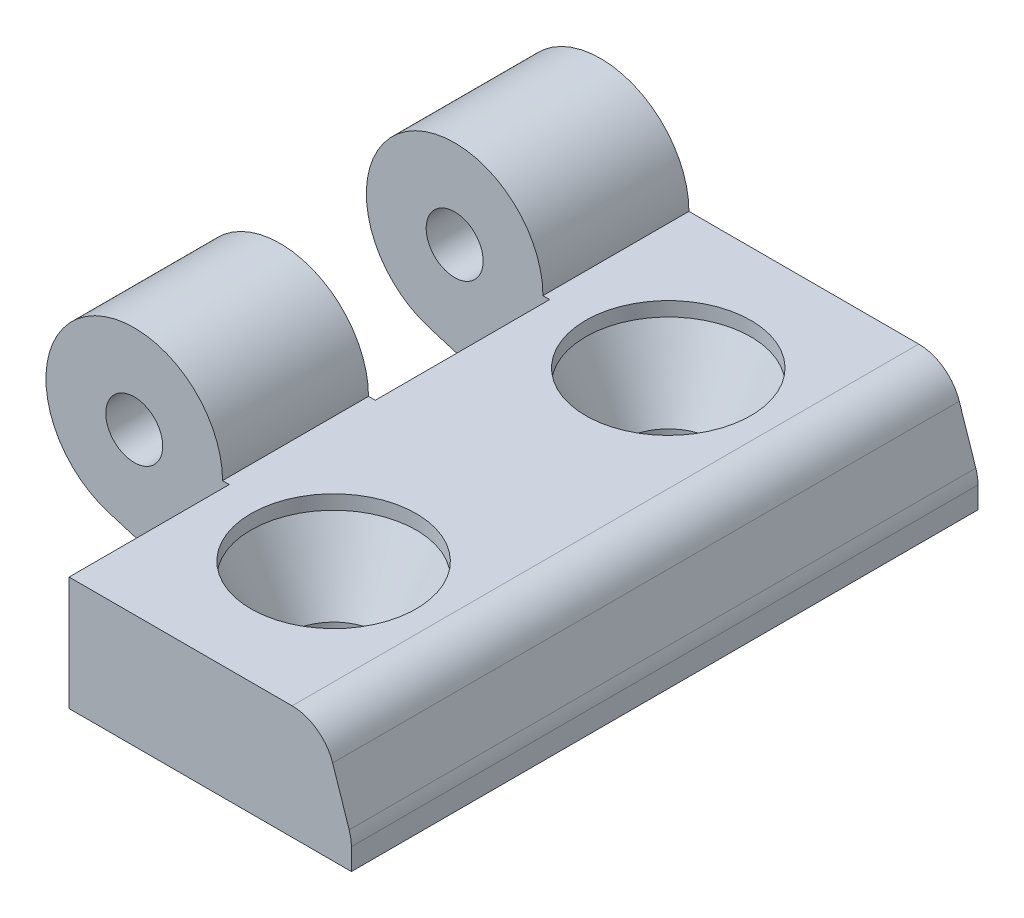
SolidWorks part; units mm, degrees
ref_plane "前视基准面" through (0, 0, 0) normal (0, 0, 1) x (1, 0, 0)
ref_plane "上视基准面" through (0, 0, 0) normal (0, 1, 0) x (1, 0, 0)
ref_plane "右视基准面" through (0, 0, 0) normal (1, 0, 0) x (0, 0, -1)
sketch "草图1" plane through (0, 0, 0) normal (0, 0, 1) x (1, 0, 0)
  line B0 (26.5, -8) -> (26.5, -6.4868)
  line B1 (6.2, 0) -> (22.3377, 0)
  line B2 (5, -8) -> (26.5, -8)
  line B3 (5, -8) -> (-1.8032, -5.932)
  line B4 (26.346, -5.5381) -> (25.1838, -2.0513)
  arc B5 (25.1838, -2.0513) -> (22.3377, 0) centre (22.3377, -3) ccw
  arc B6 (6.2, 0) -> (-1.8032, -5.932) centre (0, 0) ccw
  arc B7 (26.5, -6.4868) -> (26.346, -5.5381) centre (23.5, -6.4868) ccw
sketch_block_instance "A$C3A447B15-1"
sketch_block "A$C3A447B15"
extrude "凸台-拉伸1" add sketch "草图1" along normal mid plane 44
sketch "草图3" plane through (0, 0, 0) normal (0, 1, 0) x (1, 0, 0)
  line L0 (22.3377, -22) -> (6.2, -22) construction
  line L1 (6.6744, -22) -> (-9.0362, -22)
  line L2 (6.6744, -22) -> (6.6744, -10.75)
  line L3 (6.6744, -10.75) -> (-9.0362, -10.75)
  line L4 (-9.0362, -22) -> (-9.0362, -10.75)
  line L6 (6.6744, -0.5) -> (-10.336, -0.5)
  line L7 (6.6744, -0.5) -> (6.6744, 11.75)
  line L8 (6.6744, 11.75) -> (-10.336, 11.75)
  line L9 (-10.336, -0.5) -> (-10.336, 11.75)
  dimension "D1" = 11.25
  dimension "D2" = 10.25
  dimension "D3" = 12.25
extrude "切除-拉伸1" cut sketch "草图3" against normal through all and the other way through all
sketch "草图4" plane through (0, 0, -22) normal (0, 0, -1) x (-1, 0, 0)
  circle A0 centre (0, 0) radius 2
extrude "切除-拉伸2" cut sketch "草图4" against normal through all
ref_plane "基准面2" through (0, 0, -11.75) normal (0, 0, -1) x (-1, 0, 0)
sketch "草图5" plane through (0, 0, -11.75) normal (0, 0, -1) x (-1, 0, 0)
  line L0 (-15, 0) -> (-15, -8)
  line L1 (-22.3377, 0) -> (-6.2, 0) construction
  line L2 (-5, -8) -> (-26.5, -8) construction
  line L3 (-11.75, -8) -> (-11.75, -6)
  line L4 (-9.2, 0) -> (-9.2, -1)
  line L5 (-9.2, -1) -> (-11.75, -6)
  line L6 (-15, -8) -> (-11.75, -8)
  line L7 (-15, 0) -> (-9.2, 0)
  circle A0 centre (0, 0) radius 2 construction
  dimension "D1" = 15
  dimension "D2" = 3.25
  dimension "D3" = 2
  dimension "D4" = 5.8
  dimension "D5" = 1
revolve "切除-旋转1" cut sketch "草图5" angle 360 about L0
pattern_linear "阵列(线性)1" count 2 spacing 23.5 along (0, 0, 1) of "切除-旋转1"
